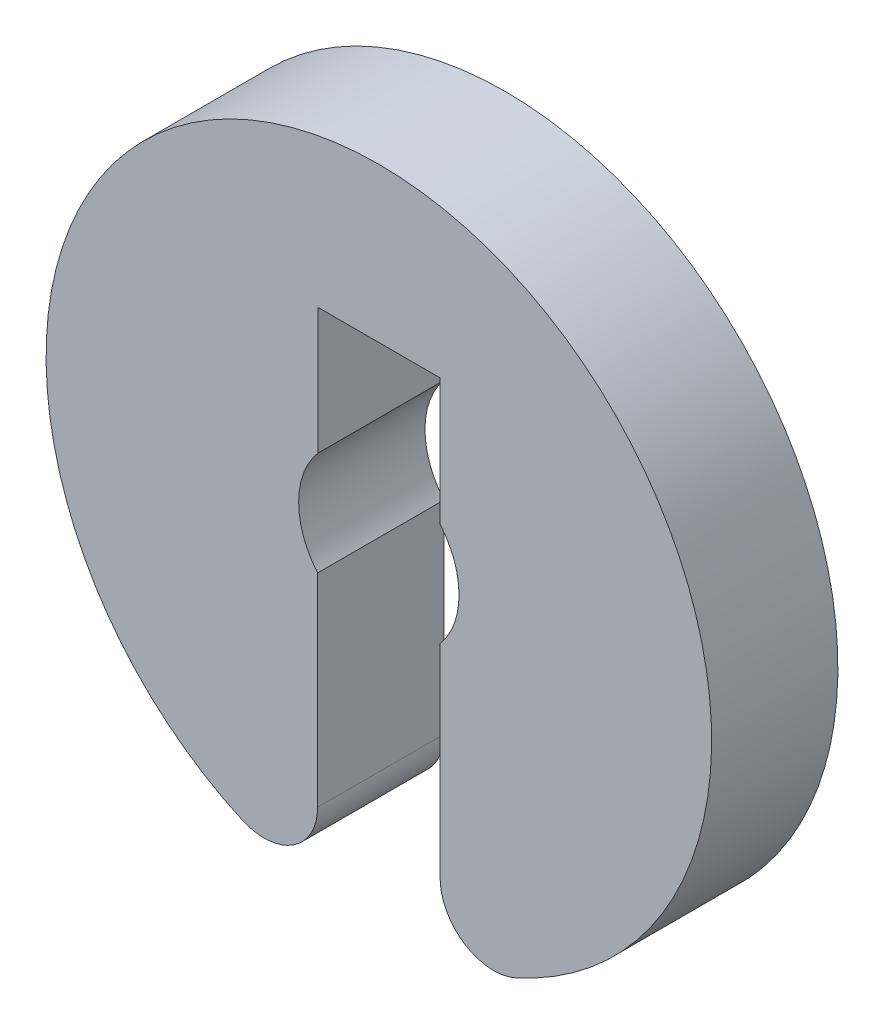
SolidWorks part; units mm, degrees
material "Acrylic (Medium-high impact)"
ref_plane "Front Plane" through (0, 0, 0) normal (0, 0, 1) x (1, 0, 0)
ref_plane "Top Plane" through (0, 0, 0) normal (0, 1, 0) x (1, 0, 0)
ref_plane "Right Plane" through (0, 0, 0) normal (1, 0, 0) x (0, 0, -1)
sketch "스케치1" plane through (0, 0, 0) normal (0, 0, 1) x (1, 0, 0)
  line L0 (0, 10.85) -> (0, 0) construction
  line L6 (-1.4475, 4.2385) -> (1.4475, 4.2385)
  line L7 (0, 0) -> (0, -4.4998) construction
  line L8 (-1.455, -7.7699) -> (1.455, -7.7699) construction
  line L9 (-1.455, -7.7699) -> (-1.455, -1.2296)
  line L10 (-1.455, -1.2296) -> (1.455, -1.2296) construction
  line L11 (1.455, -7.7699) -> (1.455, -1.2296)
  line L12 (-1.455, -7.7699) -> (1.455, -1.2296) construction
  line L13 (-1.455, -1.2296) -> (1.455, -7.7699) construction
  line L14 (-1.4475, 4.2385) -> (-1.4475, 1.2385)
  line L15 (-1.4475, 1.2385) -> (1.4475, 1.2385) construction
  line L16 (1.4475, 4.2385) -> (1.4475, 1.2385)
  line L17 (-1.4475, 4.2385) -> (1.4475, 1.2385) construction
  line L18 (-1.4475, 1.2385) -> (1.4475, 4.2385) construction
  circle A0 centre (0, 0) radius 7.905 construction
  circle A1 centre (0, 0) radius 1.905 construction
  arc A2 (-1.455, -7.7699) -> (1.455, -7.7699) centre (0, 0) cw
  arc A3 (1.455, -1.2296) -> (1.4475, 1.2385) centre (0, 0) ccw
  arc A4 (-1.4475, 1.2385) -> (-1.455, -1.2296) centre (0, 0) ccw
  point P2 (0, 10.85)
  point P5 (0, 2.7385)
  point P10 (0, -4.4998)
  dimension "D1" = 6
  dimension "D2" = 3.81
  dimension "D3" = 2.895
  dimension "D4" = 3
  dimension "D5" = 2.91
extrude "보스-돌출1" add sketch "스케치1" along normal blind 3
fillet "필렛1" radius 1.27 2 edges at (-1.455, -7.7699, 1.5) (1.455, -7.7699, 1.5)
